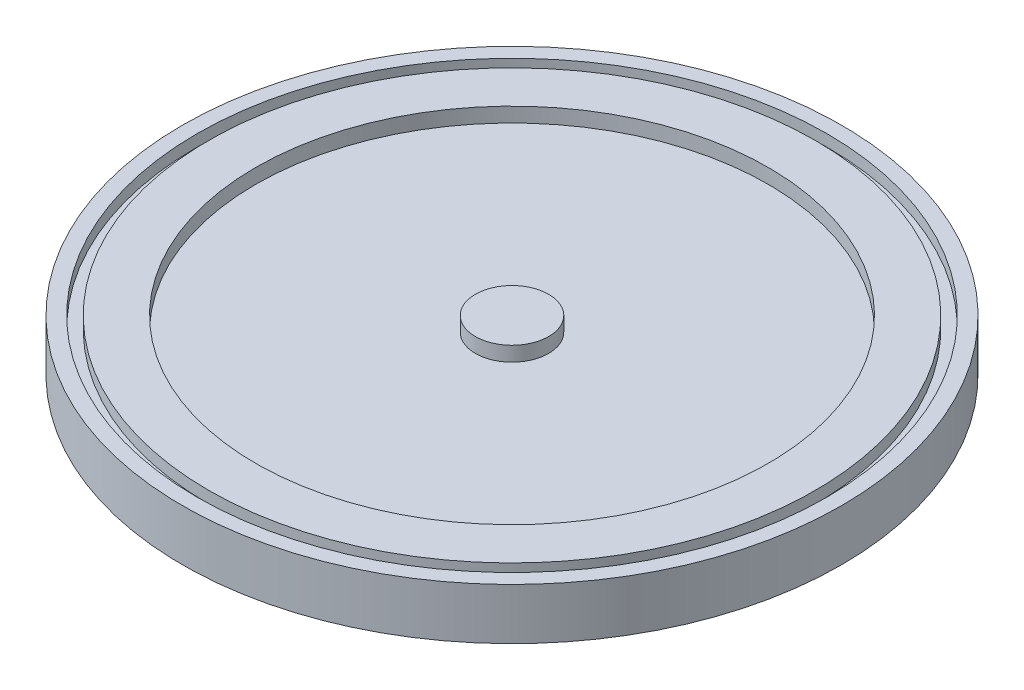
SolidWorks part; units mm, degrees
material "AISI 304"
ref_plane "Front Plane" through (0, 0, 0) normal (0, 0, 1) x (1, 0, 0)
ref_plane "Top Plane" through (0, 0, 0) normal (0, 1, 0) x (1, 0, 0)
ref_plane "Right Plane" through (0, 0, 0) normal (1, 0, 0) x (0, 0, -1)
sketch "Main Shape Profile" plane through (0, 0, 0) normal (0, 0, 1) x (1, 0, 0)
  line L1 (57.15, 0) -> (57.15, 8.89)
  line L2 (57.15, 8.89) -> (44.45, 8.89)
  line L3 (44.45, 8.89) -> (44.45, 6.35)
  line L4 (44.45, 6.35) -> (6.35, 6.35)
  line L5 (0, 8.89) -> (0, 0)
  line L6 (0, 0) -> (57.15, 0)
  line L7 (0, 0) -> (0, -50000) construction
  line L8 (0, 8.89) -> (6.35, 8.89)
  line L9 (6.35, 8.89) -> (6.35, 6.35)
  point P4 (0, 0)
  dimension "Inner Injector Diameter" = 88.9
  dimension "Kerosene Manifold Thickness" = 2.54
  dimension "Kersoene Plate Thickness" = 6.35
  dimension "Standoff Diameter" = 12.7
  dimension "Kerosene Plate Outer Diameter" = 114.3
revolve "Main Shape" add sketch "Main Shape Profile" angle 360 about L7
sketch "O Rings Profile" plane through (0, 0, 0) normal (0, 0, 1) x (1, 0, 0)
  line L0 (57.15, 8.89) -> (-57.15, 8.89) construction
  line L1 (52.578, 8.89) -> (54.61, 8.89)
  line L2 (52.578, 8.89) -> (52.578, 6.858)
  line L3 (52.578, 6.858) -> (54.61, 6.858)
  line L4 (54.61, 8.89) -> (54.61, 6.858)
  line L5 (-57.15, 0) -> (57.15, 0) construction
  line L6 (52.578, 0) -> (54.61, 0)
  line L7 (52.578, 0) -> (52.578, 2.032)
  line L8 (52.578, 2.032) -> (54.61, 2.032)
  line L9 (54.61, 0) -> (54.61, 2.032)
  line L10 (57.15, 0) -> (57.15, 8.89) construction
  line L11 (0, 0) -> (0, -50000) construction
  dimension "O Ring Depth1" = 2.032
  dimension "O Ring Width" = 2.032
  dimension "O Ring Position" = 2.54
revolve "O-Rings Cutout" cut sketch "O Rings Profile" angle 360 about L11
